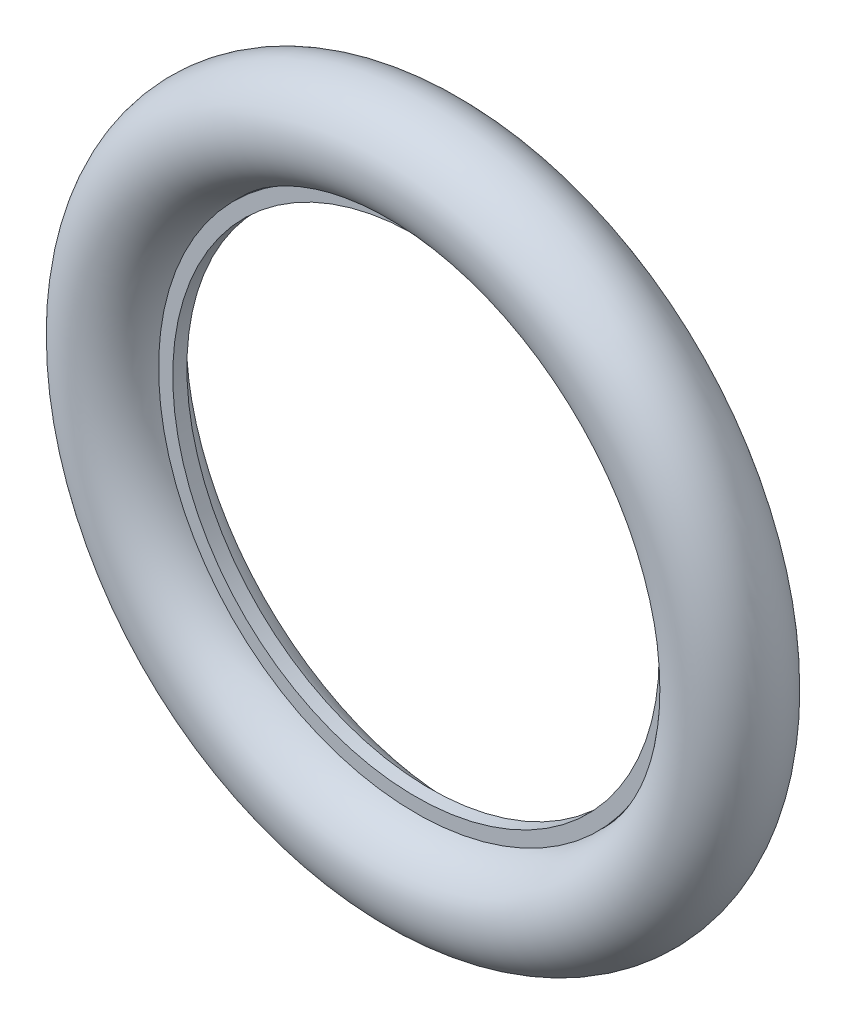
SolidWorks part; units mm, degrees
ref_plane "Front" through (0, 0, 0) normal (0, 0, 1) x (1, 0, 0)
ref_plane "Top" through (0, 0, 0) normal (0, 1, 0) x (1, 0, 0)
ref_plane "Right" through (0, 0, 0) normal (1, 0, 0) x (0, 0, -1)
sketch "Sketch1" plane through (0, 0, 0) normal (1, 0, 0) x (0, -1, 0)
  line L0 (0, -0.889) -> (0, 0.889) construction
  line L2 (-7.0409, 0) -> (7.0409, 0) construction
  line L3 (-4.6228, 0) -> (4.6228, 0) construction
  circle A0 centre (5.5118, 0) radius 0.889
  point P9 (4.6228, 0)
  point P10 (6.4008, 0)
  point P13 (5.5118, 0.889)
  point P14 (5.5118, -0.889)
  dimension "Width" = 1.778
  dimension "ID" = 9.2456
revolve "Revolve1" add sketch "Sketch1" angle 360 about L0
sketch "Sketch3" plane through (0, 0, 0) normal (0, 0, 1) x (1, 0, 0)
  circle A0 centre (0, 0) radius 4.6228
  circle A1 centre (0, 0) radius 4.3688
  dimension "D1" = 0.254
extrude "Boss-Extrude1" add sketch "Sketch3" along normal mid plane 0.254 separate body contours A0 A1
